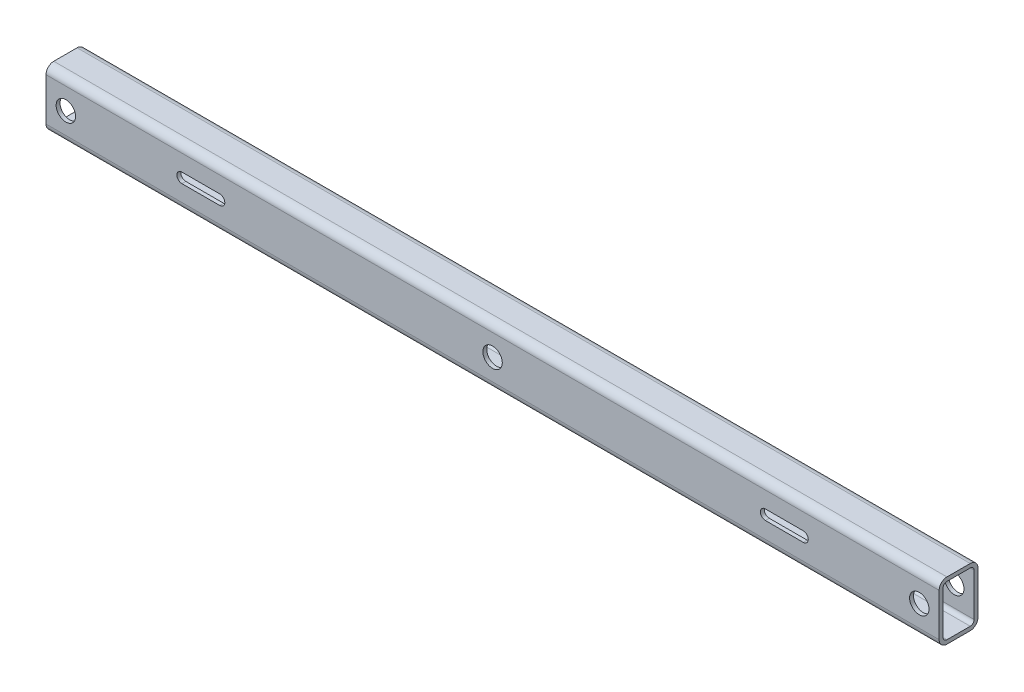
SolidWorks part; units mm, degrees
ref_plane "Front Plane" through (0, 0, 0) normal (0, 0, 1) x (1, 0, 0)
ref_plane "Top Plane" through (0, 0, 0) normal (0, 1, 0) x (1, 0, 0)
ref_plane "Right Plane" through (0, 0, 0) normal (1, 0, 0) x (0, 0, -1)
sketch "Sketch1" plane through (0, 0, 0) normal (0, 0, 1) x (1, 0, 0)
  line L1 (-1150, -75) -> (1150, -75)
  line L2 (-1150, -75) -> (-1150, 75)
  line L3 (-1150, 75) -> (1150, 75)
  line L4 (1150, -75) -> (1150, 75)
  line L5 (-1150, -75) -> (1150, 75) construction
  line L6 (-1150, 75) -> (1150, -75) construction
  point P0 (0, 0)
  dimension "D1" = 2300
  dimension "D2" = 150
extrude "Boss-Extrude1" add sketch "Sketch1" along normal blind 100
sketch "Sketch2" plane through (1150, 0, 0) normal (1, 0, 0) x (0, 0, -1)
  line L14 (-90, 65) -> (-90, -65)
  line L15 (-90, -65) -> (-10, -65)
  line L16 (-10, -65) -> (-10, 65)
  line L17 (-10, 65) -> (-90, 65)
  line L18 (-90, 65) -> (-90, -65)
  line L19 (-90, -65) -> (-10, -65)
  line L20 (-10, -65) -> (-10, 65)
  line L21 (-10, 65) -> (-90, 65)
  dimension "D1" = 10
extrude "Cut-Extrude1" cut sketch "Sketch2" against normal through all
fillet "Fillet1" radius 10 4 edges at (0, -65, 90) (0, 65, 90) (0, 65, 10) (0, -65, 10)
fillet "Fillet2" radius 20 4 edges at (0, -75, 100) (0, -75, 0) (0, 75, 100) (0, 75, 0)
sketch "Sketch3" plane through (0, 0, 0) normal (0, 0, -1) x (-1, 0, 0)
  circle A0 centre (0, 0) radius 25
  circle A1 centre (-1098.86, 0) radius 25
  circle A2 centre (1098.86, 0) radius 25
  dimension "D1" = 50
  dimension "D2" = 50
  dimension "D3" = 50
  dimension "D4" = 1098.86
  dimension "D5" = 1098.86
extrude "Cut-Extrude2" cut sketch "Sketch3" against normal through all
sketch "Sketch4" plane through (0, 0, 0) normal (0, 0, -1) x (-1, 0, 0)
  line L0 (0, 0) -> (0, -416.4924) construction
  line L1 (-799.995, 0) -> (-702.465, 0) construction
  line L2 (-799.995, 12.91) -> (-702.465, 12.91)
  line L3 (-799.995, -12.91) -> (-702.465, -12.91)
  line L4 (799.995, 0) -> (702.465, 0) construction
  line L5 (799.995, 12.91) -> (702.465, 12.91)
  line L6 (799.995, -12.91) -> (702.465, -12.91)
  arc A0 (-799.995, 12.91) -> (-799.995, -12.91) centre (-799.995, 0) ccw
  arc A1 (-702.465, -12.91) -> (-702.465, 12.91) centre (-702.465, 0) ccw
  circle A2 centre (-1098.86, 0) radius 25 construction
  arc A3 (799.995, 12.91) -> (799.995, -12.91) centre (799.995, 0) cw
  arc A4 (702.465, -12.91) -> (702.465, 12.91) centre (702.465, 0) cw
  point P6 (-751.23, 0)
  point P15 (751.23, 0)
  dimension "D3" = 12.91
  dimension "D1" = 347.63
  dimension "D2" = 97.53
extrude "Cut-Extrude3" cut sketch "Sketch4" against normal through all
